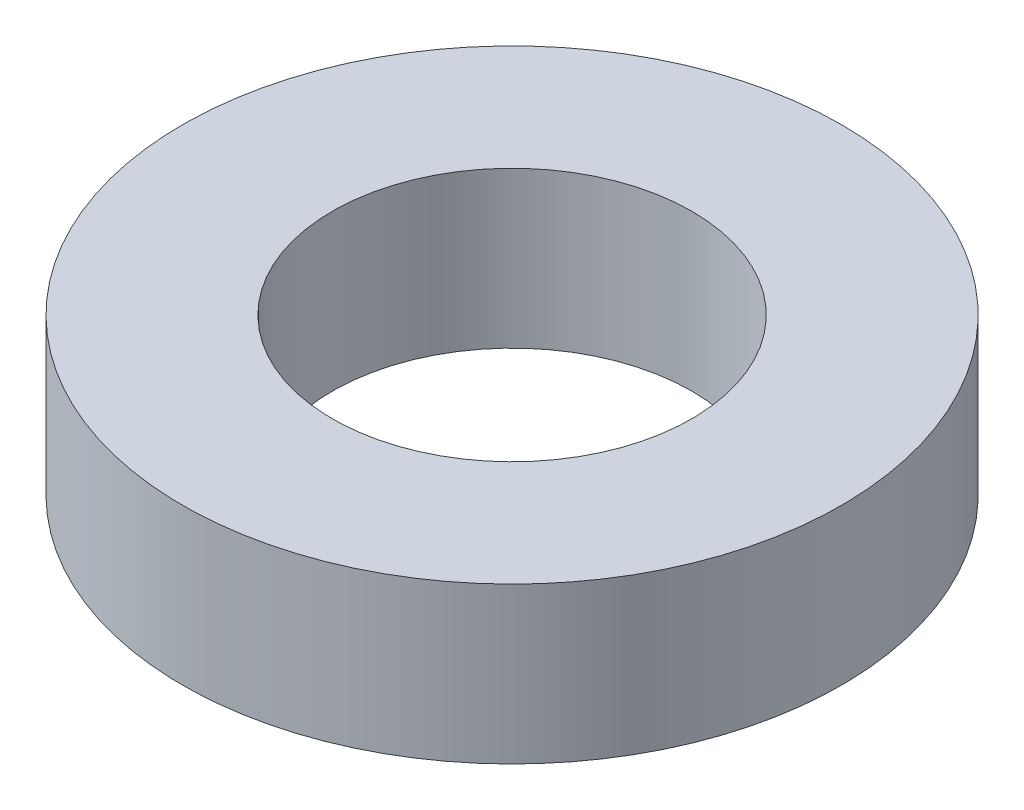
SolidWorks part; units mm, degrees
ref_plane "Front Plane" through (0, 0, 0) normal (0, 0, 1) x (1, 0, 0)
ref_plane "Top Plane" through (0, 0, 0) normal (0, 1, 0) x (1, 0, 0)
ref_plane "Right Plane" through (0, 0, 0) normal (1, 0, 0) x (0, 0, -1)
sketch "Sketch1" plane through (0, 0, 0) normal (0, 1, 0) x (1, 0, 0)
  circle A0 centre (0, 0) radius 27.5
  circle A1 centre (0, 0) radius 15
  dimension "D1" = 30
  dimension "D2" = 55
extrude "Boss-Extrude1" add sketch "Sketch1" along normal blind 13
